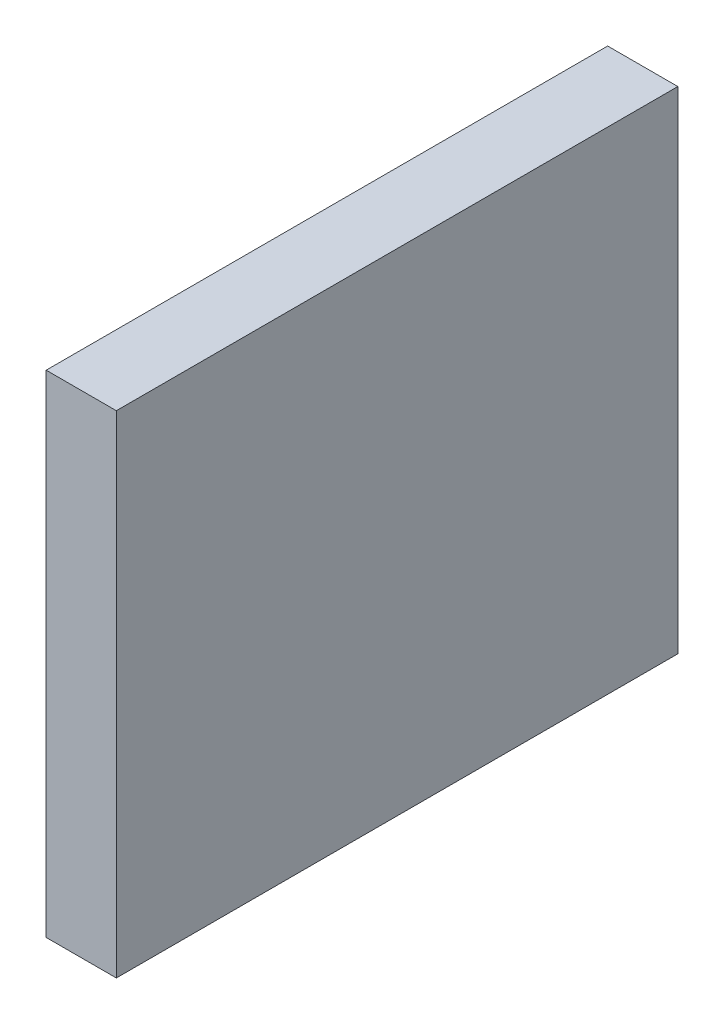
SolidWorks part; units mm, degrees
ref_plane "Front Plane" through (0, 0, 0) normal (0, 0, 1) x (1, 0, 0)
ref_plane "Top Plane" through (0, 0, 0) normal (0, 1, 0) x (1, 0, 0)
ref_plane "Right Plane" through (0, 0, 0) normal (1, 0, 0) x (0, 0, -1)
sketch "Sketch1" plane through (0, 0, 0) normal (1, 0, 0) x (0, 0, -1)
  line L1 (0, 0) -> (25.4, 0)
  line L2 (0, 0) -> (0, 22.225)
  line L3 (0, 22.225) -> (25.4, 22.225)
  line L4 (25.4, 0) -> (25.4, 22.225)
  dimension "D1" = 22.225
  dimension "D2" = 25.4
extrude "Boss-Extrude1" add sketch "Sketch1" along normal blind 3.175
